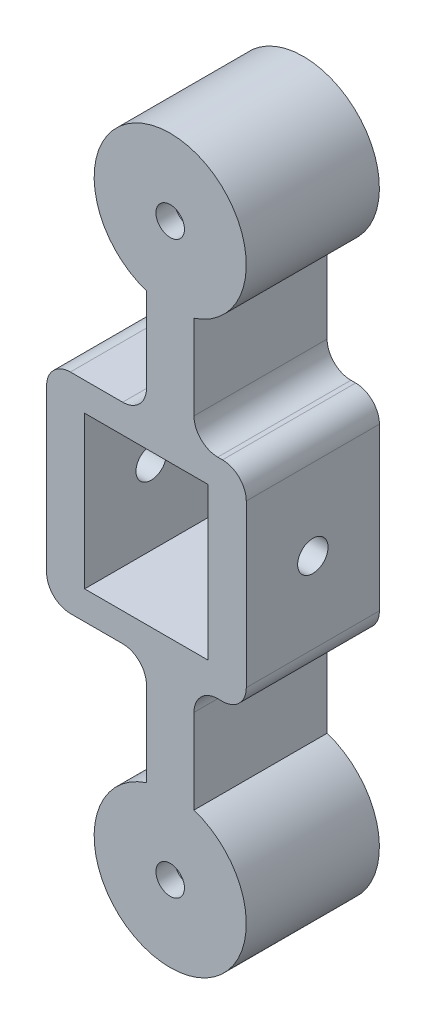
SolidWorks part; units mm, degrees
material "ABS"
ref_plane "Plano frontal" through (0, 0, 0) normal (0, 0, 1) x (1, 0, 0)
ref_plane "Plano superior" through (0, 0, 0) normal (0, 1, 0) x (1, 0, 0)
ref_plane "Plano direito" through (0, 0, 0) normal (1, 0, 0) x (0, 0, -1)
sketch "Esboço1" plane through (0, 0, 0) normal (0, 0, 1) x (1, 0, 0)
  line L0 (2.5, 52.4007) -> (2.5, 41)
  line L1 (2.5, 41) -> (8, 41)
  line L2 (-2.5, 41) -> (-13, 41)
  line L3 (-13, 41) -> (-13, 19)
  line L4 (-13, 19) -> (-2.5, 19)
  line L5 (4, 22) -> (-9, 22)
  line L6 (-9, 22) -> (-9, 38)
  line L7 (-2.5, 52.4007) -> (-2.5, 41)
  line L8 (-9, 38) -> (4, 38)
  line L9 (8, 41) -> (8, 19)
  line L10 (-2.5, 19) -> (-2.5, 7.5993)
  line L11 (4, 38) -> (4, 22)
  line L12 (8, 19) -> (2.5, 19)
  line L13 (2.5, 19) -> (2.5, 7.5993)
  line L14 (0, 60) -> (0, 0) construction
  circle A0 centre (0, 60) radius 4
  circle A1 centre (0, 0) radius 4
  arc A2 (2.5, 52.4007) -> (-2.5, 52.4007) centre (0, 60) ccw
  arc A3 (-2.5, 7.5993) -> (2.5, 7.5993) centre (0, 0) ccw
  point P11 (0, 30)
  point P15 (-9, 30)
  point P21 (-13, 30)
  dimension "D1" = 8
  dimension "D4" = 8
  dimension "D3" = 60
  dimension "D5" = 4
  dimension "D6" = 3
  dimension "D7" = 16
  dimension "D8" = 13
  dimension "D9" = 2.5
  dimension "D2" = 4
  dimension "D10" = 4
extrude "Ressalto-extrusão1" add sketch "Esboço1" along normal blind 14
sketch "Esboço3" plane through (0, 0, 14) normal (0, 0, 1) x (1, 0, 0)
  circle A0 centre (0, 60) radius 8
  circle A1 centre (0, 0) radius 8
  circle A2 centre (0, 60) radius 1.5
  circle A3 centre (0, 0) radius 1.5
  dimension "D1" = 3
extrude "Ressalto-extrusão2" add sketch "Esboço3" against normal blind 4
sketch "Esboço2" plane through (-2.5, 0, 0) normal (-1, 0, 0) x (0, 0, 1)
  line L0 (0, 30) -> (14, 30) construction
  line L4 (0, 22) -> (0, 38) construction
  line L5 (14, 22) -> (14, 38) construction
  circle A0 centre (7, 30) radius 1.6
  dimension "D1" = 3.2
extrude "Corte-extrusão1" cut sketch "Esboço2" against normal through all both and the other way through all contours A0
sketch "Esboço4" plane through (0, 0, 10) normal (0, 0, 1) x (1, 0, 0)
  line L1 (0, 56.94) -> (2.65, 58.47)
  line L2 (2.65, 58.47) -> (2.65, 61.53)
  line L3 (2.65, 61.53) -> (0, 63.06)
  line L4 (0, 63.06) -> (-2.65, 61.53)
  line L5 (-2.65, 61.53) -> (-2.65, 58.47)
  line L6 (-2.65, 58.47) -> (0, 56.94)
  line L7 (0, -3.06) -> (2.65, -1.53)
  line L8 (2.65, -1.53) -> (2.65, 1.53)
  line L9 (2.65, 1.53) -> (0, 3.06)
  line L10 (0, 3.06) -> (-2.65, 1.53)
  line L11 (-2.65, 1.53) -> (-2.65, -1.53)
  line L12 (-2.65, -1.53) -> (0, -3.06)
  circle A0 centre (0, 60) radius 2.65 construction
  circle A1 centre (0, 0) radius 2.65 construction
  dimension "D1" = 5.3
extrude "Corte-extrusão2" cut sketch "Esboço4" against normal blind 2 from offset 2
fillet "Filete1" radius 2.5 8 edges at (-2.5, 41, 7) (-2.5, 19, 7) (-13, 19, 7) (-13, 41, 7) (2.5, 41, 7) (2.5, 19, 7) (8, 19, 7) (8, 41, 7)
equation "\"D10@Esboço1\"=\"D5@Esboço1\""
